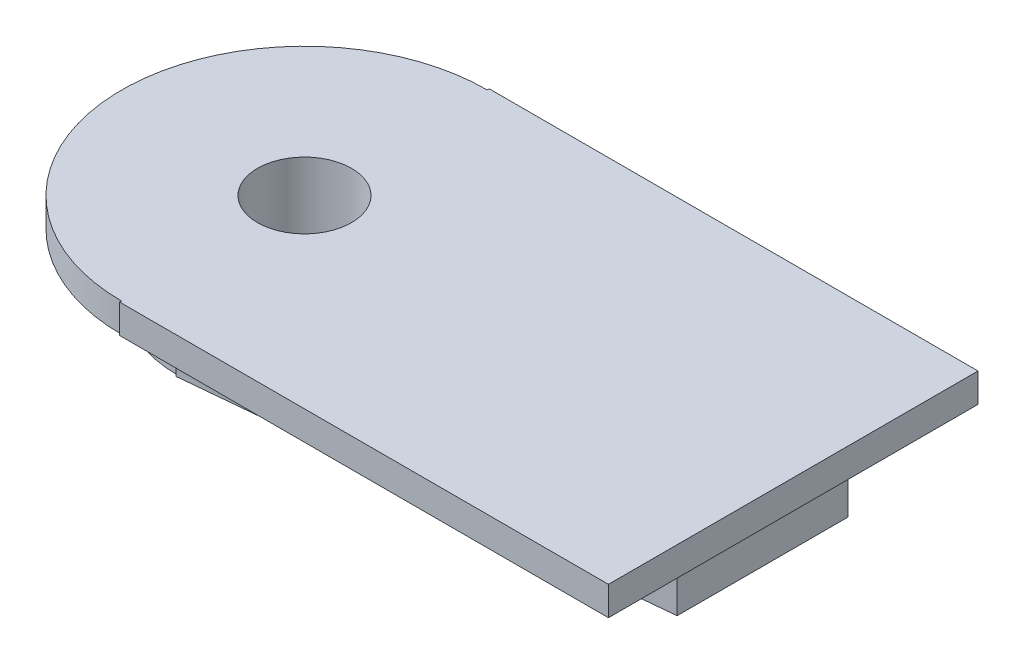
SolidWorks part; units mm, degrees
material "ABS"
ref_plane "Front Plane" through (0, 0, 0) normal (0, 0, 1) x (1, 0, 0)
ref_plane "Top Plane" through (0, 0, 0) normal (0, 1, 0) x (1, 0, 0)
ref_plane "Right Plane" through (0, 0, 0) normal (1, 0, 0) x (0, 0, -1)
sketch "Sketch1" plane through (0, 0, 0) normal (0, 1, 0) x (1, 0, 0)
  circle A0 centre (0, 0) radius 3.5
extrude "Boss-Extrude1" add sketch "Sketch1" along normal mid plane 1.75 from offset 22.625
sketch "Sketch2" plane through (0, 0, 0) normal (0, 1, 0) x (1, 0, 0)
  line L0 (0, -3.5536) -> (12.65, -2.3578)
  line L1 (12.65, -2.3578) -> (12.65, 2.3578)
  line L2 (12.65, 2.3578) -> (0, 3.5536)
  line L3 (0, 3.5536) -> (0, -3.5536)
extrude "Boss-Extrude2" add sketch "Sketch2" along normal mid plane 1.75 from offset 22.625
sketch "Sketch3" plane through (0, 0, 0) normal (0, 1, 0) x (1, 0, 0)
  circle A0 centre (0, 0) radius 5.05
extrude "Boss-Extrude3" add sketch "Sketch3" along normal mid plane 0.8 from offset 23.9
sketch "Sketch4" plane through (0, 0, 0) normal (0, 1, 0) x (1, 0, 0)
  line L1 (0, -5.1038) -> (13.5, -5.1038)
  line L2 (0, -5.1038) -> (0, 5.1038)
  line L3 (0, 5.1038) -> (13.5, 5.1038)
  line L4 (13.5, -5.1038) -> (13.5, 5.1038)
extrude "Boss-Extrude4" add sketch "Sketch4" along normal mid plane 0.8 from offset 23.9
sketch "Sketch5" plane through (0, 0, 0) normal (0, 1, 0) x (1, 0, 0)
  circle A0 centre (0, 0) radius 1.3
extrude "Cut-Extrude1" cut sketch "Sketch5" against normal mid plane 2.55 from offset 23.025
